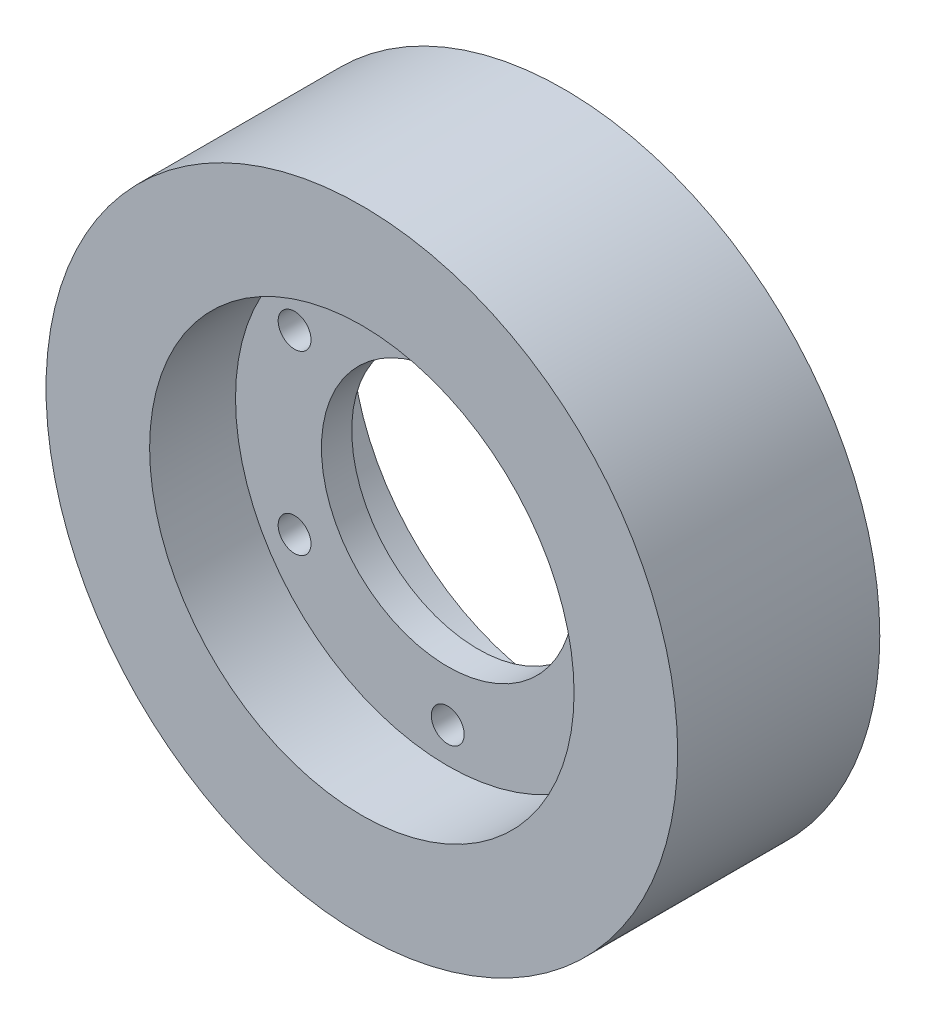
SolidWorks part; units mm, degrees
ref_plane "前视基准面" through (0, 0, 0) normal (0, 0, 1) x (1, 0, 0)
ref_plane "上视基准面" through (0, 0, 0) normal (0, 1, 0) x (1, 0, 0)
ref_plane "右视基准面" through (0, 0, 0) normal (1, 0, 0) x (0, 0, -1)
sketch "草图1" plane through (0, 0, 0) normal (0, 0, 1) x (1, 0, 0)
  circle A0 centre (0, 0) radius 25
  circle A3 centre (0, 35) radius 3.25
  circle A4 centre (30.3109, 17.5) radius 3.25
  circle A5 centre (30.3109, -17.5) radius 3.25
  circle A6 centre (0, -35) radius 3.25
  circle A7 centre (-30.3109, -17.5) radius 3.25
  circle A8 centre (-30.3109, 17.5) radius 3.25
  circle A9 centre (0, 0) radius 42
  dimension "D1" = 50
  dimension "D2" = 6
extrude "凸台-拉伸1" add sketch "草图1" along normal blind 6
sketch "草图2" plane through (0, 0, 6) normal (0, 0, 1) x (1, 0, 0)
  circle A0 centre (0, 0) radius 62.5
  circle A1 centre (0, 0) radius 42
extrude "凸台-拉伸2" add sketch "草图2" along normal mid plane 40 from offset 3
